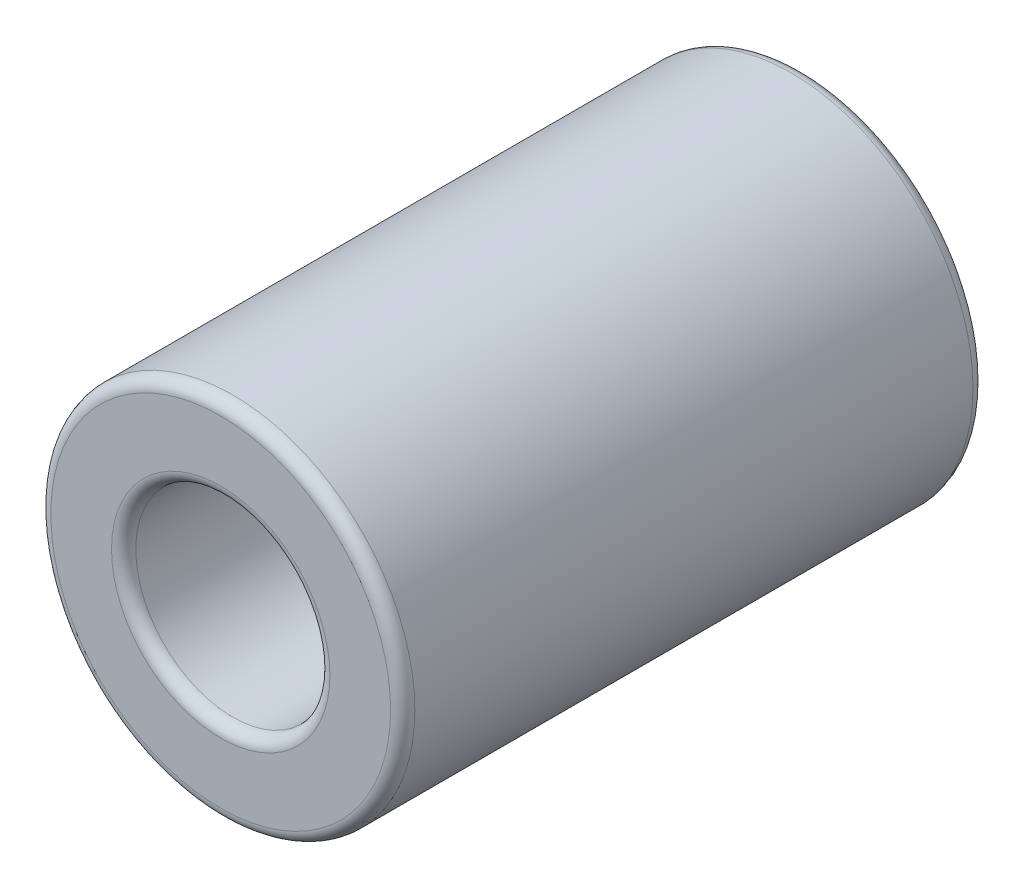
SolidWorks part; units mm, degrees
material "AISI 1015 钢，冷拔 (SS)"
ref_plane "前视基准面" through (0, 0, 0) normal (0, 0, 1) x (1, 0, 0)
ref_plane "上视基准面" through (0, 0, 0) normal (0, 1, 0) x (1, 0, 0)
ref_plane "右视基准面" through (0, 0, 0) normal (1, 0, 0) x (0, 0, -1)
other "Configuration Table"
sketch "草图1" plane through (0, 0, 0) normal (0, 0, 1) x (1, 0, 0)
  circle A0 centre (0, 0) radius 4
  circle A1 centre (0, 0) radius 7.5
  dimension "D1" = 8
  dimension "D2" = 15
extrude "凸台-拉伸1" add sketch "草图1" along normal blind 24
fillet "圆角1" radius 0.5 4 edges at (7.5, 0, 0) (7.5, 0, 24) (4, 0, 0) (4, 0, 24)
